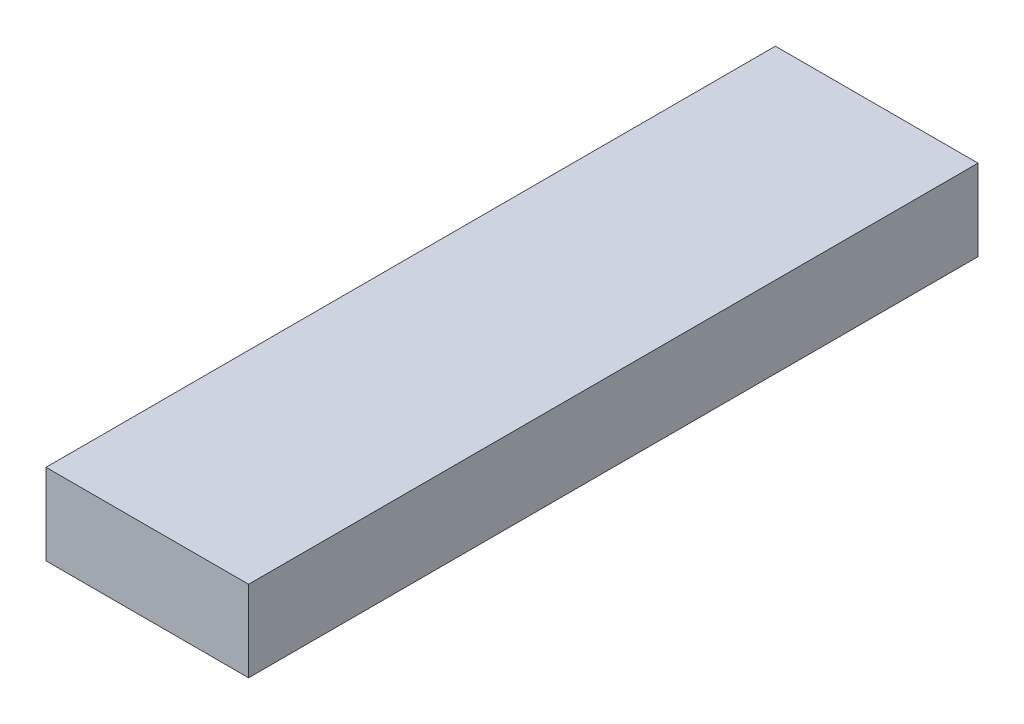
SolidWorks part; units mm, degrees
ref_plane "Front Plane" through (0, 0, 0) normal (0, 0, 1) x (1, 0, 0)
ref_plane "Top Plane" through (0, 0, 0) normal (0, 1, 0) x (1, 0, 0)
ref_plane "Right Plane" through (0, 0, 0) normal (1, 0, 0) x (0, 0, -1)
sketch "Sketch1" plane through (0, 0, 0) normal (0, 1, 0) x (1, 0, 0)
  line L1 (-25, -90) -> (25, -90)
  line L2 (-25, -90) -> (-25, 90)
  line L3 (-25, 90) -> (25, 90)
  line L4 (25, -90) -> (25, 90)
  line L5 (0, 90) -> (0, -90) construction
  line L6 (-25, 0) -> (25, 0) construction
  point P0 (0, 0)
  dimension "D1" = 50
  dimension "D2" = 180
extrude "Boss-Extrude1" add sketch "Sketch1" along normal blind 20
